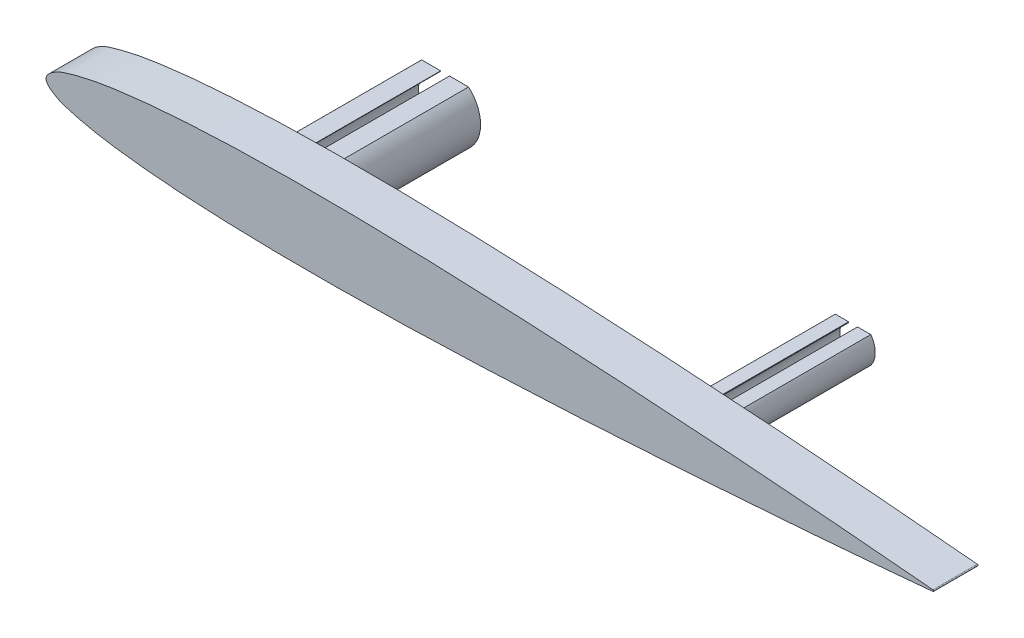
SolidWorks part; units mm, degrees
material "ABS generico"
ref_plane "Piano frontale" through (0, 0, 0) normal (0, 0, 1) x (1, 0, 0)
ref_plane "Piano superiore" through (0, 0, 0) normal (0, 1, 0) x (1, 0, 0)
ref_plane "Piano destro" through (0, 0, 0) normal (1, 0, 0) x (0, 0, -1)
curve "Curva1"
  spline degree 3 poles (100, 0.084, 0) (98.3335, 0.2367, 0) (95.0012, 0.5422, 0) (88.3356, 1.1109, 0) (80.0033, 1.7636, 0) (70.003, 2.4579, 0) (60.0031, 3.0617, 0) (50.003, 3.5521, 0) (40.0026, 3.9029, 0) (31.667, 4.0253, 0) (24.9992, 3.9769, 0) (19.9978, 3.845, 0) (14.9934, 3.5925, 0) (10.8272, 3.2377, 0) (7.4891, 2.814, 0) (4.9936, 2.4037, 0) (2.8496, 1.8679, 0) (1.1654, 1.321, 0) (-0.6646, 0, 0) (1.1654, -1.321, 0) (2.8496, -1.8679, 0) (4.9936, -2.4037, 0) (7.4891, -2.814, 0) (10.8272, -3.2377, 0) (14.9934, -3.5925, 0) (19.9978, -3.845, 0) (24.9992, -3.9769, 0) (31.667, -4.0253, 0) (40.0026, -3.9029, 0) (50.003, -3.5521, 0) (60.0031, -3.0617, 0) (70.003, -2.4579, 0) (80.0033, -1.7636, 0) (88.3356, -1.1109, 0) (95.0012, -0.5422, 0) (98.3335, -0.2367, 0) (100, -0.084, 0) knots 0 0 0 0 0.024876 0.049742 0.099443 0.149112 0.198751 0.248359 0.297937 0.347491 0.372267 0.397051 0.421859 0.446731 0.45922 0.471791 0.48456 0.491195 0.5 0.508805 0.51544 0.528209 0.54078 0.553269 0.578141 0.602949 0.627733 0.652509 0.702063 0.751641 0.801249 0.850888 0.900557 0.950258 0.975124 1 1 1 1
sketch "Schizzo1" plane through (0, 0, 0) normal (0, 0, 1) x (1, 0, 0)
  arc A0 (100, 0.084) -> (100, -0.084) centre (100, 0) cw
  spline S0 degree 3 poles (774.5938, 2905.893) (370.1816, -60.6448) (232.5901, -11.1972) (88.3356, 1.1109) (80.0033, 1.7636) (70.003, 2.4579) (60.0031, 3.0617) (50.003, 3.5521) (40.0026, 3.9029) (31.667, 4.0253) (24.9992, 3.9769) (19.9978, 3.845) (14.9934, 3.5925) (10.8272, 3.2377) (7.4891, 2.814) (4.9936, 2.4037) (2.8496, 1.8679) (1.1654, 1.321) (-0.6646, 0) (1.1654, -1.321) (2.8496, -1.8679) (4.9936, -2.4037) (7.4891, -2.814) (10.8272, -3.2377) (14.9934, -3.5925) (19.9978, -3.845) (24.9992, -3.9769) (31.667, -4.0253) (40.0026, -3.9029) (50.003, -3.5521) (60.0031, -3.0617) (70.003, -2.4579) (80.0033, -1.7636) (88.3356, -1.1109) (232.5893, 11.1971) (370.1799, 60.6442) (774.5865, -2905.8392) knots -2.052665 -2.052665 -2.052665 -2.052665 0.024876 0.049742 0.099443 0.149112 0.198751 0.248359 0.297937 0.347491 0.372267 0.397051 0.421859 0.446731 0.45922 0.471791 0.48456 0.491195 0.5 0.508805 0.51544 0.528209 0.54078 0.553269 0.578141 0.602949 0.627733 0.652509 0.702063 0.751641 0.801249 0.850888 0.900557 0.950258 0.975124 3.052652 3.052652 3.052652 3.052652 only from (100, 0.084) to (100, -0.084) construction
  spline S1 degree 3 poles (100, 0.084) (98.3335, 0.2367) (95.0012, 0.5422) (88.3356, 1.1109) (80.0033, 1.7636) (70.003, 2.4579) (60.0031, 3.0617) (50.003, 3.5521) (40.0026, 3.9029) (31.667, 4.0253) (24.9992, 3.9769) (19.9978, 3.845) (14.9934, 3.5925) (10.8272, 3.2377) (7.4891, 2.814) (4.9936, 2.4037) (2.8496, 1.8679) (1.1654, 1.321) (-0.6646, 0) (1.1654, -1.321) (2.8496, -1.8679) (4.9936, -2.4037) (7.4891, -2.814) (10.8272, -3.2377) (14.9934, -3.5925) (19.9978, -3.845) (24.9992, -3.9769) (31.667, -4.0253) (40.0026, -3.9029) (50.003, -3.5521) (60.0031, -3.0617) (70.003, -2.4579) (80.0033, -1.7636) (88.3356, -1.1109) (95.0012, -0.5422) (98.3335, -0.2367) (100, -0.084) knots 0 0 0 0 0.024876 0.049742 0.099443 0.149112 0.198751 0.248359 0.297937 0.347491 0.372267 0.397051 0.421859 0.446731 0.45922 0.471791 0.48456 0.491195 0.5 0.508805 0.51544 0.528209 0.54078 0.553269 0.578141 0.602949 0.627733 0.652509 0.702063 0.751641 0.801249 0.850888 0.900557 0.950258 0.975124 1 1 1 1
extrude "CorpoCentina" add sketch "Schizzo1" along normal blind 5
sketch "Schizzo2" plane through (0, 0, 0) normal (0, 0, 1) x (1, 0, 0)
  line L0 (25.5, -3) -> (24.5, 3) construction
  line L1 (22.3542, -3) -> (24.5, -3)
  line L3 (22.3542, 3) -> (24.5, 3)
  line L6 (24.5, -3) -> (24.5, -2.958)
  line L8 (25.5, -3) -> (25.5, -2.958)
  line L9 (25.5, 3) -> (24.5, -3) construction
  line L10 (25.5, -3) -> (27.6458, -3)
  line L11 (24.5, 2.958) -> (24.5, 3)
  line L12 (25.5, 2.958) -> (25.5, 3)
  line L13 (25.5, 3) -> (27.6458, 3)
  arc A0 (25.5, -2.958) -> (25.5, 2.958) centre (25, 0) ccw
  arc A1 (27.6458, -3) -> (27.6458, 3) centre (25, 0) ccw
  arc A2 (22.3542, 3) -> (22.3542, -3) centre (25, 0) ccw
  arc A3 (24.5, 2.958) -> (24.5, -2.958) centre (25, 0) ccw
  dimension "D1" = 6
  dimension "D3" = 8
  dimension "D2" = 25
  dimension "D4" = 1
sketch "Schizzo3" plane through (0, 0, 0) normal (0, 0, -1) x (-1, 0, 0)
  line L2 (-71, 0) -> (-100, 0) construction
  line L3 (-70.5, -1.5) -> (-71.5, 1.5) construction
  line L4 (-69, -1.5) -> (-70.5, -1.5)
  line L6 (-69, 1.5) -> (-70.5, 1.5)
  line L9 (-70.5, -1.5) -> (-70.5, -1.4142)
  line L11 (-71.5, -1.5) -> (-71.5, -1.4142)
  line L12 (-71.5, -1.5) -> (-70.5, 1.5) construction
  line L13 (-71.5, -1.5) -> (-73, -1.5)
  line L14 (-71.5, 1.4142) -> (-71.5, 1.5)
  line L15 (-70.5, 1.4142) -> (-70.5, 1.5)
  line L16 (-71.5, 1.5) -> (-73, 1.5)
  arc A4 (-70.5, -1.4142) -> (-70.5, 1.4142) centre (-71, 0) ccw
  arc A5 (-69, -1.5) -> (-69, 1.5) centre (-71, 0) ccw
  arc A6 (-73, 1.5) -> (-73, -1.5) centre (-71, 0) ccw
  arc A7 (-71.5, 1.4142) -> (-71.5, -1.4142) centre (-71, 0) ccw
  dimension "D1" = 3
  dimension "D2" = 29
  dimension "D3" = 5
  dimension "D4" = 1
extrude "AggancioFoam" add sketch "Schizzo3" along normal blind 15
extrude "AggancioLongherone" add sketch "Schizzo2" against normal blind 15
